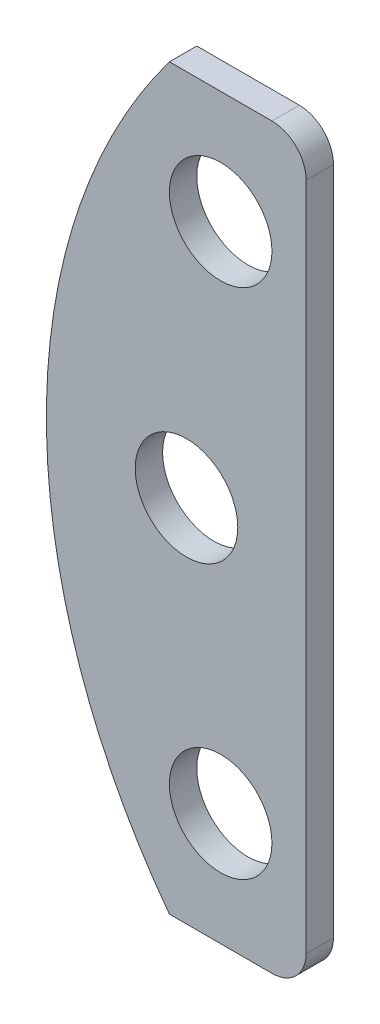
SolidWorks part; units mm, degrees
ref_plane "Plano frontal" through (0, 0, 0) normal (0, 0, 1) x (1, 0, 0)
ref_plane "Plano superior" through (0, 0, 0) normal (0, 1, 0) x (1, 0, 0)
ref_plane "Plano direito" through (0, 0, 0) normal (1, 0, 0) x (0, 0, -1)
sketch "Esboço1" plane through (0, 0, 0) normal (0, 0, 1) x (1, 0, 0)
  line L1 (-72, -54) -> (-52, -54)
  line L2 (-52, -54) -> (-52, 54)
  line L3 (-52, 54) -> (-72, 54)
  arc A0 (-72, 54) -> (-72, -54) centre (0, 0) ccw
  dimension "D1" = 180
  dimension "D2" = 108
  dimension "D3" = 20
extrude "Ressalto-extrusão1" add sketch "Esboço1" along normal blind 4
sketch "Esboço2" plane through (0, 0, 0) normal (0, 0, -1) x (-1, 0, 0)
  line L0 (52, 0) -> (69.5, 0)
  line L1 (52, -54) -> (52, 54) construction
  line L2 (52, -54) -> (64.5, -54)
  line L3 (72, -54) -> (52, -54) construction
  line L4 (64.5, -54) -> (64.5, -37.5)
  circle A0 centre (69.5, 0) radius 7.5
  circle A1 centre (64.5, -37.5) radius 7.5
  circle A2 centre (64.5, 37.5) radius 7.5
  dimension "D2" = 15
  dimension "D5" = 15
  dimension "D1" = 17.5
  dimension "D3" = 12.5
  dimension "D4" = 16.5
extrude "Corte-extrusão1" cut sketch "Esboço2" against normal blind 10
fillet "Filete1" radius 5 2 edges at (-52, -54, 2) (-52, 54, 2)
